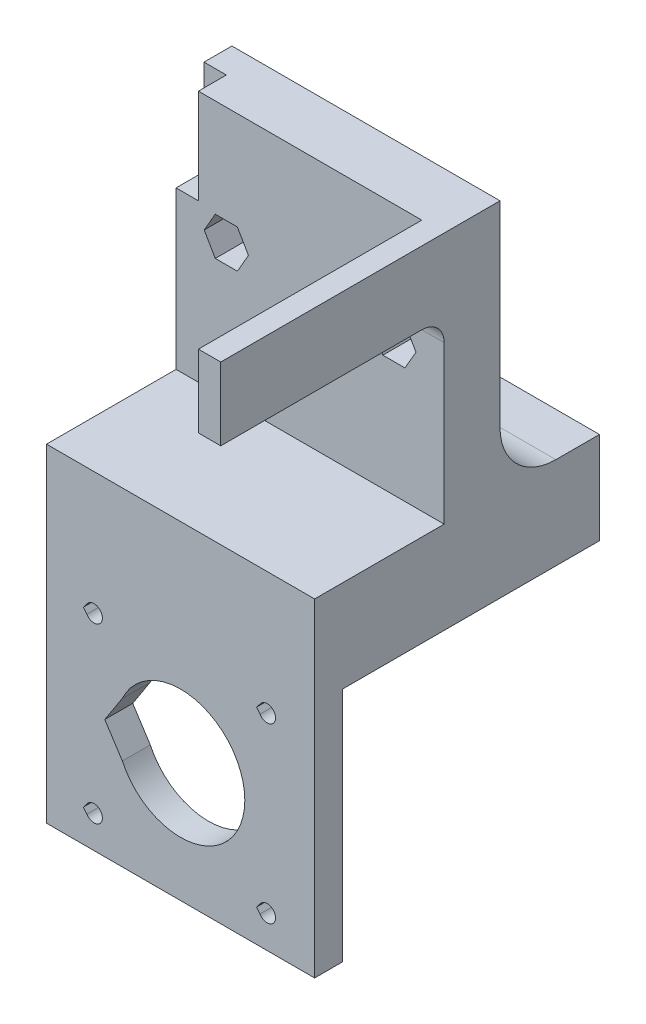
SolidWorks part; units mm, degrees
ref_plane "Front Plane" through (0, 0, 0) normal (0, 0, 1) x (1, 0, 0)
ref_plane "Top Plane" through (0, 0, 0) normal (0, 1, 0) x (1, 0, 0)
ref_plane "Right Plane" through (0, 0, 0) normal (1, 0, 0) x (0, 0, -1)
sketch "Sketch1" plane through (0, 0, 0) normal (0, 0, 1) x (1, 0, 0)
  line L1 (0, 0) -> (48, 0)
  line L2 (0, 0) -> (0, 53)
  line L3 (0, 53) -> (48, 53)
  line L4 (48, 0) -> (48, 53)
  dimension "D1" = 53
  dimension "D2" = 48
extrude "Boss-Extrude1" add sketch "Sketch1" along normal blind 10
sketch "Sketch2" plane through (0, 0, 0) normal (0, 0, -1) x (-1, 0, 0)
  line L0 (0, 53) -> (0, 0) construction
  line L1 (-48, 0) -> (0, 0)
  line L2 (-48, 0) -> (-48, -5.6163)
  line L3 (-48, -5.6163) -> (0, -5.6163)
  line L4 (0, 0) -> (0, -5.6163)
  dimension "D1" = 5.6163
extrude "Boss-Extrude2" add sketch "Sketch2" against normal blind 33.1918
sketch "Sketch4" plane through (0, 0, 10) normal (0, 0, 1) x (1, 0, 0)
  line L1 (0, 53) -> (4, 53)
  line L2 (0, 53) -> (0, 43)
  line L3 (0, 43) -> (4, 43)
  line L4 (4, 53) -> (4, 43)
  line L5 (48, 53) -> (44, 53)
  line L6 (48, 53) -> (48, 43)
  line L7 (48, 43) -> (44, 43)
  line L8 (44, 53) -> (44, 43)
  dimension "D1" = 10
  dimension "D2" = 4
extrude "Boss-Extrude4" add sketch "Sketch4" along normal blind 40
sketch "Sketch5" plane through (0, 0, 10) normal (0, 0, 1) x (1, 0, 0)
  line L0 (48, 0) -> (48, 43) construction
  line L1 (0, 0) -> (48, 0)
  line L2 (0, 0) -> (0, 10.8609)
  line L3 (0, 10.8609) -> (48, 10.8609)
  line L4 (48, 0) -> (48, 10.8609)
  dimension "D1" = 10.8609
extrude "Boss-Extrude5" add sketch "Sketch5" along normal up to surface (23.1918 mm away) up to face at (24, -2.8082, 33.1918)
sketch "Sketch6" plane through (0, -5.6163, 0) normal (0, -1, 0) x (1, 0, 0)
  line L0 (0, 0) -> (0, 28.1918) construction
  line L1 (0, 33.1918) -> (0, 0) construction
  line L2 (48, 33.1918) -> (48, 0) construction
  line L3 (0, 28.1918) -> (48, 28.1918)
  line L4 (0, 28.1918) -> (0, 33.1918)
  line L5 (0, 33.1918) -> (48, 33.1918)
  line L6 (48, 28.1918) -> (48, 33.1918)
  line L8 (48, 33.1918) -> (0, 33.1918) construction
  dimension "D2" = 5
extrude "Boss-Extrude6" add sketch "Sketch6" along normal blind 42.3
sketch "Sketch7" plane through (0, 0, 0) normal (-1, 0, 0) x (0, 0, 1)
  line L0 (33.1918, 10.8609) -> (10, 10.8609) construction
  line L1 (0, -5.6163) -> (-12.8082, -5.6163)
  line L2 (0, -5.6163) -> (0, 10.8609)
  line L3 (0, 10.8609) -> (-12.8082, 10.8609)
  line L4 (-12.8082, -5.6163) -> (-12.8082, 10.8609)
  line L5 (28.1918, -47.9163) -> (28.1918, -5.6163) construction
  dimension "D1" = 41
extrude "Boss-Extrude7" add sketch "Sketch7" against normal up to surface (48 mm away) up to face at (48, 10.6657, 24.2767)
sketch "Sketch8" plane through (0, 0, 28.1918) normal (0, 0, -1) x (-1, 0, 0)
  line L0 (-24, -26.6163) -> (-24, -5.6163) construction
  line L1 (0, -5.6163) -> (-48, -5.6163) construction
  line L3 (-8.5, -42.1163) -> (-39.5, -42.1163) construction
  line L4 (-8.5, -42.1163) -> (-8.5, -11.1163) construction
  line L5 (-8.5, -11.1163) -> (-39.5, -11.1163) construction
  line L6 (-39.5, -42.1163) -> (-39.5, -11.1163) construction
  line L7 (-8.5, -42.1163) -> (-39.5, -11.1163) construction
  line L8 (-8.5, -11.1163) -> (-39.5, -42.1163) construction
  circle A0 centre (-24, -26.6163) radius 11.5
  circle A1 centre (-39.5, -11.1163) radius 1.5
  circle A2 centre (-39.5, -42.1163) radius 1.5
  circle A3 centre (-8.5, -11.1163) radius 1.5
  circle A4 centre (-8.5, -42.1163) radius 1.5
  dimension "D2" = 23
  dimension "D4" = 3
  dimension "D1" = 21
  dimension "D3" = 31
extrude "Cut-Extrude1" cut sketch "Sketch8" against normal up to next
fillet "Fillet1" radius 10 1 edges at (24, 10.8609, 0)
fillet "Fillet2" radius 4 2 edges at (2, 43, 10) (46, 43, 10)
sketch "Sketch9" plane through (48, 0, 0) normal (1, 0, 0) x (0, 0, -1)
  line L1 (12.8082, 10.8609) -> (17.8082, 10.8609)
  line L2 (12.8082, 10.8609) -> (12.8082, -5.6163)
  line L3 (12.8082, -5.6163) -> (17.8082, -5.6163)
  line L4 (17.8082, 10.8609) -> (17.8082, -5.6163)
  line L5 (-28.1918, -5.6163) -> (12.8082, -5.6163) construction
  dimension "D1" = 5
extrude "Boss-Extrude9" add sketch "Sketch9" against normal up to surface (48 mm away) contours L4 L3 L2 L1 up to face at (0, 13.3569, 15.8852)
sketch "Sketch10" plane through (0, 0, 10) normal (0, 0, 1) x (1, 0, 0)
  line L0 (4, 53) -> (9, 35) construction
  line L1 (9, 35) -> (39, 35) construction
  line L2 (39, 35) -> (44, 53) construction
  line L3 (44, 53) -> (4, 53) construction
  line L4 (44, 53) -> (44, 43) construction
  line L6 (7.0203, 38.429) -> (5.0405, 35)
  line L7 (5.0405, 35) -> (7.0203, 31.571)
  line L8 (7.0203, 31.571) -> (10.9797, 31.571)
  line L9 (10.9797, 31.571) -> (12.9595, 35)
  line L10 (12.9595, 35) -> (10.9797, 38.429)
  line L11 (10.9797, 38.429) -> (7.0203, 38.429)
  line L12 (37.0203, 31.571) -> (40.9797, 31.571)
  line L13 (40.9797, 31.571) -> (42.9595, 35)
  line L14 (42.9595, 35) -> (40.9797, 38.429)
  line L15 (40.9797, 38.429) -> (37.0203, 38.429)
  line L16 (37.0203, 38.429) -> (35.0405, 35)
  line L17 (35.0405, 35) -> (37.0203, 31.571)
  circle A0 centre (9, 35) radius 3.429 construction
  circle A1 centre (39, 35) radius 3.429 construction
  point P3 (0, 0)
  dimension "D1" = 6.858
  dimension "D2" = 30
  dimension "D3" = 18
extrude "Cut-Extrude2" cut sketch "Sketch10" against normal blind 6
sketch "Sketch11" plane through (0, 0, 4) normal (0, 0, 1) x (1, 0, 0)
  circle A0 centre (9, 35) radius 1.9304
  circle A1 centre (39, 35) radius 1.9304
  dimension "D1" = 3.8608
extrude "Cut-Extrude3" cut sketch "Sketch11" against normal blind 6
sketch "Sketch12" plane through (0, 53, 0) normal (0, 1, 0) x (1, 0, 0)
  line L0 (0, 0) -> (0, -50)
  line L1 (0, -50) -> (4, -50)
  line L2 (4, -50) -> (4, -10)
  line L3 (4, -10) -> (44, -10)
  line L4 (44, -10) -> (44, -50)
  line L5 (44, -50) -> (48, -50)
  line L6 (48, -50) -> (48, 0)
  line L7 (48, 0) -> (0, 0)
extrude "Boss-Extrude11" add sketch "Sketch12" along normal blind 3
sketch "Sketch14" plane through (0, 0, 0) normal (-1, 0, 0) x (0, 0, 1)
  line L1 (50, 56) -> (5, 56)
  line L2 (50, 56) -> (50, 39)
  line L3 (50, 39) -> (5, 39)
  line L4 (5, 56) -> (5, 39)
  dimension "D1" = 45
extrude "Cut-Extrude4" cut sketch "Sketch14" against normal up to surface (4 mm away) up to face at (4, 47.5657, 26.6343)
sketch "Sketch15" plane through (0, 0, 28.1918) normal (0, 0, -1) x (-1, 0, 0)
  line L0 (-39.5, -11.1163) -> (-8.5, -11.1163) construction
  line L1 (-24, -26.6163) -> (-6.5318, -26.6163) construction
  line L2 (-38.2091, -10.3523) -> (-37.602, -11.1163)
  line L3 (-38.2091, -11.8803) -> (-37.602, -11.1163)
  line L4 (-7.2091, -10.3523) -> (-6.602, -11.1163)
  line L5 (-7.2091, -11.8803) -> (-6.602, -11.1163)
  line L6 (-7.2091, -10.3523) -> (-6.602, -11.1163)
  line L7 (-7.2091, -11.8803) -> (-6.602, -11.1163)
  line L8 (-38.2091, -10.3523) -> (-37.602, -11.1163)
  line L9 (-38.2091, -11.8803) -> (-37.602, -11.1163)
  line L10 (-38.2091, -10.3523) -> (-37.602, -11.1163)
  line L11 (-38.2091, -11.8803) -> (-37.602, -11.1163)
  line L12 (-7.2091, -10.3523) -> (-6.602, -11.1163)
  line L13 (-7.2091, -11.8803) -> (-6.602, -11.1163)
  line L14 (-7.2091, -10.3523) -> (-6.602, -11.1163)
  line L15 (-7.2091, -11.8803) -> (-6.602, -11.1163)
  line L16 (-38.2091, -10.3523) -> (-37.602, -11.1163)
  line L17 (-38.2091, -11.8803) -> (-37.602, -11.1163)
  line L18 (-38.2091, -10.3523) -> (-37.602, -11.1163)
  line L19 (-38.2091, -11.8803) -> (-37.602, -11.1163)
  line L20 (-7.2091, -10.3523) -> (-6.602, -11.1163)
  line L21 (-7.2091, -11.8803) -> (-6.602, -11.1163)
  line L22 (-7.2091, -10.3523) -> (-6.602, -11.1163)
  line L23 (-7.2091, -11.8803) -> (-6.602, -11.1163)
  line L24 (-38.2091, -10.3523) -> (-37.602, -11.1163)
  line L25 (-38.2091, -11.8803) -> (-37.602, -11.1163)
  line L26 (-38.2091, -10.3523) -> (-37.602, -11.1163)
  line L27 (-38.2091, -11.8803) -> (-37.602, -11.1163)
  line L28 (-7.2091, -10.3523) -> (-6.602, -11.1163)
  line L29 (-7.2091, -11.8803) -> (-6.602, -11.1163)
  line L30 (-7.2091, -10.3523) -> (-6.602, -11.1163)
  line L31 (-7.2091, -11.8803) -> (-6.602, -11.1163)
  line L32 (-38.2091, -10.3523) -> (-37.602, -11.1163)
  line L33 (-38.2091, -11.8803) -> (-37.602, -11.1163)
  line L34 (-39.5, -42.1163) -> (-8.5, -42.1163) construction
  line L35 (-38.2091, -41.3523) -> (-37.602, -42.1163)
  line L36 (-38.2091, -42.8803) -> (-37.602, -42.1163)
  line L37 (-7.2091, -41.3523) -> (-6.602, -42.1163)
  line L38 (-7.2091, -42.8803) -> (-6.602, -42.1163)
  line L39 (-7.2091, -41.3523) -> (-6.602, -42.1163)
  line L40 (-7.2091, -42.8803) -> (-6.602, -42.1163)
  line L41 (-38.2091, -41.3523) -> (-37.602, -42.1163)
  line L42 (-38.2091, -42.8803) -> (-37.602, -42.1163)
  line L43 (-38.2091, -41.3523) -> (-37.602, -42.1163)
  line L44 (-38.2091, -42.8803) -> (-37.602, -42.1163)
  line L45 (-7.2091, -41.3523) -> (-6.602, -42.1163)
  line L46 (-7.2091, -42.8803) -> (-6.602, -42.1163)
  line L47 (-7.2091, -41.3523) -> (-6.602, -42.1163)
  line L48 (-7.2091, -42.8803) -> (-6.602, -42.1163)
  line L49 (-38.2091, -41.3523) -> (-37.602, -42.1163)
  line L50 (-38.2091, -42.8803) -> (-37.602, -42.1163)
  line L51 (-38.2091, -41.3523) -> (-37.602, -42.1163)
  line L52 (-38.2091, -42.8803) -> (-37.602, -42.1163)
  line L53 (-7.2091, -41.3523) -> (-6.602, -42.1163)
  line L54 (-7.2091, -42.8803) -> (-6.602, -42.1163)
  line L55 (-7.2091, -41.3523) -> (-6.602, -42.1163)
  line L56 (-7.2091, -42.8803) -> (-6.602, -42.1163)
  line L57 (-38.2091, -41.3523) -> (-37.602, -42.1163)
  line L58 (-38.2091, -42.8803) -> (-37.602, -42.1163)
  line L59 (-38.2091, -41.3523) -> (-37.602, -42.1163)
  line L60 (-38.2091, -42.8803) -> (-37.602, -42.1163)
  line L61 (-7.2091, -41.3523) -> (-6.602, -42.1163)
  line L62 (-7.2091, -42.8803) -> (-6.602, -42.1163)
  line L63 (-7.2091, -41.3523) -> (-6.602, -42.1163)
  line L64 (-7.2091, -42.8803) -> (-6.602, -42.1163)
  line L65 (-38.2091, -41.3523) -> (-37.602, -42.1163)
  line L66 (-38.2091, -42.8803) -> (-37.602, -42.1163)
  line L67 (-13.5773, -21.7566) -> (-10.4303, -26.6163)
  line L69 (-13.5773, -31.476) -> (-10.4303, -26.6163)
  arc A1 (-38.2091, -11.8803) -> (-38.2091, -10.3523) centre (-39.5, -11.1163) ccw
  arc A2 (-7.2091, -11.8803) -> (-7.2091, -10.3523) centre (-8.5, -11.1163) ccw
  arc A3 (-7.2091, -41.3523) -> (-7.2091, -42.8803) centre (-8.5, -42.1163) cw
  arc A4 (-38.2091, -41.3523) -> (-38.2091, -42.8803) centre (-39.5, -42.1163) cw
  arc A6 (-13.5773, -31.476) -> (-13.5773, -21.7566) centre (-24, -26.6163) ccw
  circle M11 centre (-8.5, -42.1163) radius 1.5
  circle M12 centre (-8.5, -11.1163) radius 1.5
  circle M13 centre (-39.5, -42.1163) radius 1.5
  circle M14 centre (-39.5, -11.1163) radius 1.5
  circle M15 centre (-24, -26.6163) radius 11.5
  dimension "D1" = 2
extrude "Cut-Extrude5" cut sketch "Sketch15" against normal up to next contours L69 L67 M15 | L5 L4 M12 | L3 L2 M14 | L36 L35 M13 | L38 L37 M11
